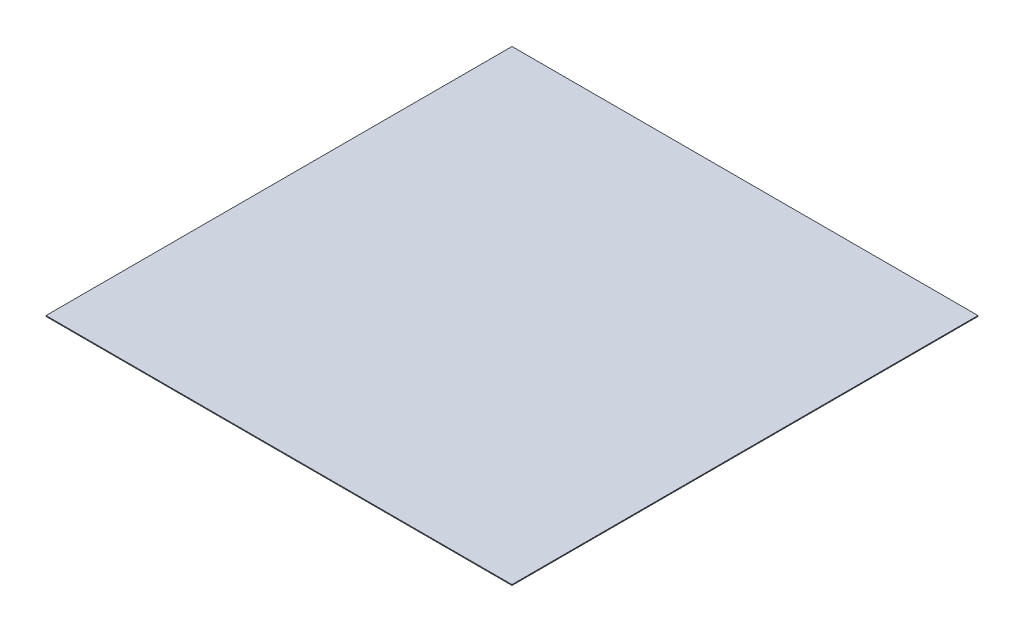
SolidWorks part; units mm, degrees
material "STYCAST 2850FT/Catalyst 23LV"
ref_plane "Front Plane" through (0, 0, 0) normal (0, 0, 1) x (1, 0, 0)
ref_plane "Top Plane" through (0, 0, 0) normal (0, 1, 0) x (1, 0, 0)
ref_plane "Right Plane" through (0, 0, 0) normal (1, 0, 0) x (0, 0, -1)
sketch "Sketch1" plane through (0, 0, 0) normal (0, 1, 0) x (1, 0, 0)
  line L1 (-70, -70) -> (70, -70)
  line L2 (-70, -70) -> (-70, 70)
  line L3 (-70, 70) -> (70, 70)
  line L4 (70, -70) -> (70, 70)
  line L5 (-70, -70) -> (70, 70) construction
  line L6 (-70, 70) -> (70, -70) construction
  point P0 (0, 0)
  dimension "D1" = 140
extrude "Boss-Extrude1" add sketch "Sketch1" along normal mid plane 0.25
equation "\"panel_width\"= 140mm"
equation "\"finger_joint_width\" = 40mm"
equation "\"D1@Sketch1\"=\"panel_width\""
